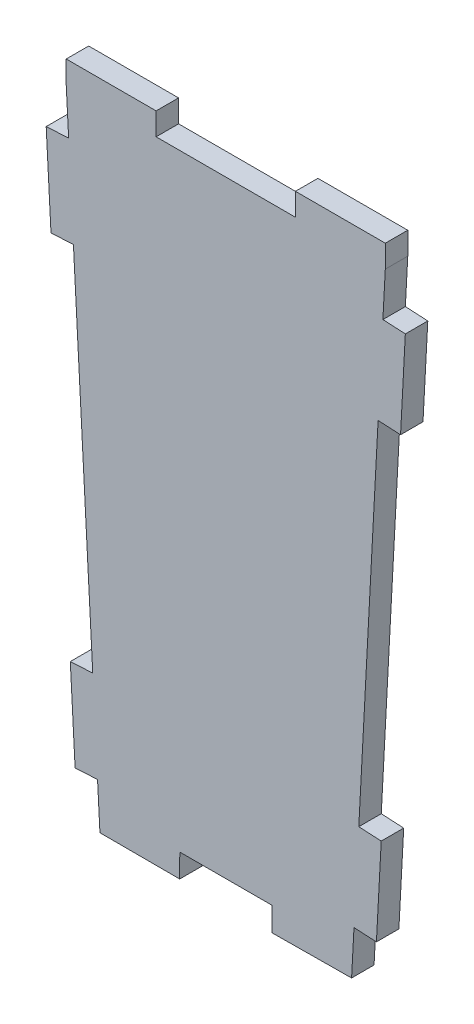
SolidWorks part; units mm, degrees
ref_plane "Front Plane" through (0, 0, 0) normal (0, 0, 1) x (1, 0, 0)
ref_plane "Top Plane" through (0, 0, 0) normal (0, 1, 0) x (1, 0, 0)
ref_plane "Right Plane" through (0, 0, 0) normal (1, 0, 0) x (0, 0, -1)
sketch "Model" plane through (0, 0, 0) normal (0, 0, 1) x (1, 0, 0)
  line L0 (624.1056, -123.6795) -> (619.8071, -43.234)
  line L1 (663.9688, -153.7844) -> (663.9688, -148.4763)
  line L2 (614.8142, -43.5008) -> (619.8071, -43.234)
  line L3 (643.4573, -153.686) -> (625.7069, -153.6468)
  line L4 (625.7069, -153.6468) -> (625.1727, -143.651)
  line L5 (619.1127, -123.9463) -> (624.1056, -123.6795)
  line L6 (669.2063, -13.2767) -> (638.2063, -13.2767)
  line L7 (620.1799, -143.9178) -> (619.1127, -123.9463)
  line L8 (693.6656, -23.5293) -> (692.5984, -43.5008)
  line L9 (689.2063, -13.2767) -> (688.6727, -23.2625)
  line L10 (618.7399, -23.2625) -> (613.747, -23.5293)
  line L11 (681.7063, -153.6367) -> (663.9688, -153.7844)
  line L12 (669.2063, -8.2767) -> (669.2063, -13.2767)
  line L13 (682.2399, -143.651) -> (687.2327, -143.9178)
  line L14 (613.747, -23.5293) -> (614.8142, -43.5008)
  line L15 (681.7063, -153.6367) -> (682.2399, -143.651)
  line L16 (687.2327, -143.9178) -> (688.2999, -123.9463)
  line L17 (688.2999, -123.9463) -> (683.307, -123.6795)
  line L18 (683.307, -123.6795) -> (687.6056, -43.234)
  line L19 (692.5984, -43.5008) -> (687.6056, -43.234)
  line L20 (688.6727, -23.2625) -> (693.6656, -23.5293)
  line L21 (689.2063, -13.2767) -> (689.2063, -8.2767)
  line L22 (689.2063, -8.2767) -> (669.2063, -8.2767)
  line L23 (638.2063, -8.2767) -> (638.2063, -13.2767)
  line L24 (618.2063, -8.2767) -> (638.2063, -8.2767)
  line L25 (618.2063, -13.2767) -> (618.2063, -8.2767)
  line L26 (618.2063, -13.2767) -> (618.7399, -23.2625)
  line L27 (625.1727, -143.651) -> (620.1799, -143.9178)
  line L28 (643.4688, -148.483) -> (643.4573, -153.686)
  line L29 (663.9688, -148.4763) -> (643.4688, -148.483)
  line L30 (658.0332, -74.751) -> (657.5462, -75.0663)
  line L31 (661.2425, -82.805) -> (661.7202, -82.499)
  line L32 (653.6499, -83.0922) -> (652.7679, -83.0219)
  line L33 (661.8794, -82.1307) -> (661.8794, -75.4378)
  line L34 (661.7202, -82.499) -> (661.8396, -82.3227)
  line L35 (657.4244, -82.318) -> (657.5462, -82.4928)
  line L36 (659.6316, -83.0922) -> (658.7638, -83.0204)
  line L37 (657.5462, -75.0663) -> (657.4244, -75.2451)
  line L38 (657.3838, -75.4378) -> (657.3838, -76.0497)
  line L39 (651.4021, -75.4378) -> (651.4423, -75.2455)
  line L40 (658.7638, -83.0204) -> (658.0332, -82.805)
  line L41 (661.8794, -75.4378) -> (661.8396, -75.2404)
  line L42 (661.2425, -74.751) -> (660.5214, -74.545)
  line L43 (655.737, -82.5006) -> (655.2546, -82.8112)
  line L44 (657.4244, -82.318) -> (657.3838, -82.1307)
  line L45 (654.5319, -83.0219) -> (653.6499, -83.0922)
  line L46 (652.7679, -83.0219) -> (652.0452, -82.8112)
  line L47 (651.4021, -81.5188) -> (651.4021, -82.1307)
  line L48 (659.6316, -83.0922) -> (660.5089, -83.0204)
  line L49 (654.5319, -83.0219) -> (655.2546, -82.8112)
  line L50 (655.737, -82.5006) -> (655.8575, -82.323)
  line L51 (655.8575, -82.323) -> (655.8977, -82.1307)
  line L52 (655.8977, -82.1307) -> (655.8977, -75.4378)
  line L53 (651.4021, -82.1307) -> (651.4423, -82.323)
  line L54 (657.3838, -82.1307) -> (657.3838, -81.5188)
  line L55 (659.6316, -74.4763) -> (658.745, -74.545)
  line L56 (661.8396, -82.3227) -> (661.8794, -82.1307)
  line L57 (658.745, -74.545) -> (658.0332, -74.751)
  line L58 (657.4244, -75.2451) -> (657.3838, -75.4378)
  line L59 (657.5462, -82.4928) -> (658.0332, -82.805)
  line L60 (651.5629, -82.5006) -> (651.4423, -82.323)
  line L61 (660.5214, -74.545) -> (659.6316, -74.4763)
  line L62 (660.5089, -83.0204) -> (661.2425, -82.805)
  line L63 (661.8396, -75.2404) -> (661.7202, -75.0601)
  line L64 (661.7202, -75.0601) -> (661.2425, -74.751)
  line L65 (651.5629, -82.5006) -> (652.0452, -82.8112)
  line L66 (651.5629, -75.0679) -> (651.4423, -75.2455)
  line L67 (646.774, -74.5466) -> (647.656, -74.4763)
  line L68 (646.0513, -74.7573) -> (646.774, -74.5466)
  line L69 (652.7679, -74.5466) -> (652.0452, -74.7573)
  line L70 (647.656, -74.4763) -> (648.538, -74.5466)
  line L71 (649.7431, -75.0679) -> (649.2607, -74.7573)
  line L72 (655.737, -75.0679) -> (655.2546, -74.7573)
  line L73 (655.8575, -75.2455) -> (655.737, -75.0679)
  line L74 (649.4668, -79.368) -> (649.0047, -79.6209)
  line L75 (647.656, -79.8207) -> (646.774, -79.7505)
  line L76 (649.8636, -75.2455) -> (649.7431, -75.0679)
  line L77 (646.0513, -79.5398) -> (645.569, -79.2291)
  line L78 (652.0452, -74.7573) -> (651.5629, -75.0679)
  line L79 (645.569, -79.2291) -> (645.4484, -79.0516)
  line L80 (649.9038, -75.4378) -> (649.8636, -75.2455)
  line L81 (645.4082, -75.4378) -> (645.4484, -75.2455)
  line L82 (655.2546, -74.7573) -> (654.5319, -74.5466)
  line L83 (651.4021, -78.7843) -> (651.4021, -75.4378)
  line L84 (646.0513, -74.7573) -> (645.569, -75.0679)
  line L85 (645.5581, -83.0922) -> (649.9038, -83.0922)
  line L86 (649.0047, -79.6209) -> (647.656, -79.8207)
  line L87 (645.4484, -75.2455) -> (645.569, -75.0679)
  line L88 (654.5319, -74.5466) -> (653.6499, -74.4763)
  line L89 (645.4082, -75.4378) -> (645.4082, -78.8591)
  line L90 (653.625, -78.7843) -> (651.4021, -78.7843)
  line L91 (649.9038, -83.0922) -> (649.9038, -78.8591)
  line L92 (646.0513, -79.5398) -> (646.774, -79.7505)
  line L93 (645.4484, -79.0516) -> (645.4082, -78.8591)
  line L94 (653.6499, -74.4763) -> (652.7679, -74.5466)
  line L95 (648.538, -74.5466) -> (649.2607, -74.7573)
  line L96 (649.9038, -78.8591) -> (649.4668, -79.368)
  line L97 (655.8977, -75.4378) -> (655.8575, -75.2455)
  line L98 (660.2799, -72.4763) -> (660.82, -72.4763)
  line L99 (660.82, -72.4763) -> (659.7492, -72.4763)
  line L100 (659.7492, -72.4763) -> (660.2799, -72.4763)
  line L101 (660.2799, -72.4763) -> (660.2799, -70.3224)
  line L102 (660.2799, -70.3224) -> (660.2799, -72.4763)
  line L103 (659.3215, -70.3224) -> (659.3215, -72.4763)
  line L104 (659.3215, -72.4763) -> (659.3215, -71.4149)
  line L105 (659.3215, -71.4149) -> (658.2039, -71.4149)
  line L106 (658.2039, -71.4149) -> (658.2039, -72.4763)
  line L107 (658.2039, -72.4763) -> (658.2039, -70.3224)
  line L108 (658.2039, -70.3224) -> (658.2039, -71.415)
  line L109 (658.2039, -71.415) -> (659.3215, -71.415)
  line L110 (659.3215, -71.415) -> (659.3215, -70.3224)
  line L111 (657.823, -72.4794) -> (657.823, -70.3224)
  line L112 (657.323, -70.7157) -> (657.323, -70.5627)
  line L113 (657.323, -70.5627) -> (657.313, -70.5146)
  line L114 (657.313, -70.5146) -> (657.2829, -70.4703)
  line L115 (657.2829, -70.4703) -> (657.1623, -70.3926)
  line L116 (657.1623, -70.3926) -> (656.9816, -70.3399)
  line L117 (656.9816, -70.3399) -> (656.7611, -70.3224)
  line L118 (656.7611, -70.3224) -> (656.5406, -70.3399)
  line L119 (656.5406, -70.3399) -> (656.3599, -70.3926)
  line L120 (656.3599, -70.3926) -> (656.2393, -70.4703)
  line L121 (656.2393, -70.4703) -> (656.2092, -70.5146)
  line L122 (656.2092, -70.5146) -> (656.1991, -70.5627)
  line L123 (656.1991, -70.5627) -> (656.1929, -71.1996)
  line L124 (656.1929, -71.1996) -> (656.2211, -71.3254)
  line L125 (656.2211, -71.3254) -> (656.3026, -71.4157)
  line L126 (656.3026, -71.4157) -> (656.4373, -71.4706)
  line L127 (656.4373, -71.4706) -> (656.6253, -71.4899)
  line L128 (656.6253, -71.4899) -> (656.966, -71.4985)
  line L129 (656.966, -71.4985) -> (657.1295, -71.518)
  line L130 (657.1295, -71.518) -> (657.2747, -71.5999)
  line L131 (657.2747, -71.5999) -> (657.311, -71.6485)
  line L132 (657.311, -71.6485) -> (657.323, -71.7022)
  line L133 (657.323, -71.7022) -> (657.323, -72.2359)
  line L134 (657.323, -72.2359) -> (657.313, -72.284)
  line L135 (657.313, -72.284) -> (657.2829, -72.3284)
  line L136 (657.2829, -72.3284) -> (657.1623, -72.4061)
  line L137 (657.1623, -72.4061) -> (656.9816, -72.4588)
  line L138 (656.9816, -72.4588) -> (656.7611, -72.4763)
  line L139 (656.7611, -72.4763) -> (656.5406, -72.4588)
  line L140 (656.5406, -72.4588) -> (656.3599, -72.4061)
  line L141 (656.3599, -72.4061) -> (656.2393, -72.3284)
  line L142 (656.2393, -72.3284) -> (656.2092, -72.284)
  line L143 (656.2092, -72.284) -> (656.1991, -72.2359)
  line L144 (656.1991, -72.2359) -> (656.1991, -72.083)
  line L145 (656.1991, -72.083) -> (656.1991, -72.2359)
  line L146 (656.1991, -72.2359) -> (656.2092, -72.284)
  line L147 (656.2092, -72.284) -> (656.2393, -72.3284)
  line L148 (656.2393, -72.3284) -> (656.3599, -72.4061)
  line L149 (656.3599, -72.4061) -> (656.5406, -72.4588)
  line L150 (656.5406, -72.4588) -> (656.7611, -72.4763)
  line L151 (656.7611, -72.4763) -> (656.9816, -72.4588)
  line L152 (656.9816, -72.4588) -> (657.1623, -72.4061)
  line L153 (657.1623, -72.4061) -> (657.2829, -72.3284)
  line L154 (657.2829, -72.3284) -> (657.313, -72.284)
  line L155 (657.313, -72.284) -> (657.323, -72.2359)
  line L156 (657.323, -72.2359) -> (657.323, -71.7022)
  line L157 (657.323, -71.7022) -> (657.311, -71.6485)
  line L158 (657.311, -71.6485) -> (657.2747, -71.5999)
  line L159 (657.2747, -71.5999) -> (657.1295, -71.518)
  line L160 (657.1295, -71.518) -> (656.966, -71.4985)
  line L161 (656.966, -71.4985) -> (656.6253, -71.4899)
  line L162 (656.6253, -71.4899) -> (656.4373, -71.4706)
  line L163 (656.4373, -71.4706) -> (656.3026, -71.4157)
  line L164 (656.3026, -71.4157) -> (656.2211, -71.3254)
  line L165 (656.2211, -71.3254) -> (656.1929, -71.1996)
  line L166 (656.1929, -71.1996) -> (656.1991, -70.5627)
  line L167 (656.1991, -70.5627) -> (656.2092, -70.5146)
  line L168 (656.2092, -70.5146) -> (656.2393, -70.4703)
  line L169 (656.2393, -70.4703) -> (656.3599, -70.3926)
  line L170 (656.3599, -70.3926) -> (656.5406, -70.3399)
  line L171 (656.5406, -70.3399) -> (656.7611, -70.3224)
  line L172 (656.7611, -70.3224) -> (656.9816, -70.3399)
  line L173 (656.9816, -70.3399) -> (657.1623, -70.3926)
  line L174 (657.1623, -70.3926) -> (657.2829, -70.4703)
  line L175 (657.2829, -70.4703) -> (657.313, -70.5146)
  line L176 (657.313, -70.5146) -> (657.323, -70.5627)
  line L177 (657.323, -70.5627) -> (657.323, -70.7157)
  line L178 (654.5791, -70.7157) -> (654.5791, -70.5627)
  line L179 (654.5791, -70.5627) -> (654.5691, -70.5146)
  line L180 (654.5691, -70.5146) -> (654.539, -70.4703)
  line L181 (654.539, -70.4703) -> (654.4184, -70.3926)
  line L182 (654.4184, -70.3926) -> (654.2377, -70.3399)
  line L183 (654.2377, -70.3399) -> (654.0172, -70.3224)
  line L184 (654.0172, -70.3224) -> (653.7967, -70.3399)
  line L185 (653.7967, -70.3399) -> (653.616, -70.3926)
  line L186 (653.616, -70.3926) -> (653.4954, -70.4703)
  line L187 (653.4954, -70.4703) -> (653.4653, -70.5146)
  line L188 (653.4653, -70.5146) -> (653.4552, -70.5627)
  line L189 (653.4552, -70.5627) -> (653.449, -71.1996)
  line L190 (653.449, -71.1996) -> (653.4772, -71.3254)
  line L191 (653.4772, -71.3254) -> (653.5587, -71.4157)
  line L192 (653.5587, -71.4157) -> (653.6934, -71.4706)
  line L193 (653.6934, -71.4706) -> (653.8814, -71.4899)
  line L194 (653.8814, -71.4899) -> (654.2221, -71.4985)
  line L195 (654.2221, -71.4985) -> (654.3856, -71.518)
  line L196 (654.3856, -71.518) -> (654.5308, -71.5999)
  line L197 (654.5308, -71.5999) -> (654.567, -71.6485)
  line L198 (654.567, -71.6485) -> (654.5791, -71.7022)
  line L199 (654.5791, -71.7022) -> (654.5791, -72.2359)
  line L200 (654.5791, -72.2359) -> (654.5691, -72.284)
  line L201 (654.5691, -72.284) -> (654.539, -72.3284)
  line L202 (654.539, -72.3284) -> (654.4184, -72.4061)
  line L203 (654.4184, -72.4061) -> (654.2377, -72.4588)
  line L204 (654.2377, -72.4588) -> (654.0172, -72.4763)
  line L205 (654.0172, -72.4763) -> (653.7967, -72.4588)
  line L206 (653.7967, -72.4588) -> (653.616, -72.4061)
  line L207 (653.616, -72.4061) -> (653.4954, -72.3284)
  line L208 (653.4954, -72.3284) -> (653.4653, -72.284)
  line L209 (653.4653, -72.284) -> (653.4552, -72.2359)
  line L210 (653.4552, -72.2359) -> (653.4552, -72.083)
  line L211 (653.4552, -72.083) -> (653.4552, -72.2359)
  line L212 (653.4552, -72.2359) -> (653.4653, -72.284)
  line L213 (653.4653, -72.284) -> (653.4954, -72.3284)
  line L214 (653.4954, -72.3284) -> (653.616, -72.4061)
  line L215 (653.616, -72.4061) -> (653.7967, -72.4588)
  line L216 (653.7967, -72.4588) -> (654.0172, -72.4763)
  line L217 (654.0172, -72.4763) -> (654.2377, -72.4588)
  line L218 (654.2377, -72.4588) -> (654.4184, -72.4061)
  line L219 (654.4184, -72.4061) -> (654.539, -72.3284)
  line L220 (654.539, -72.3284) -> (654.5691, -72.284)
  line L221 (654.5691, -72.284) -> (654.5791, -72.2359)
  line L222 (654.5791, -72.2359) -> (654.5791, -71.7022)
  line L223 (654.5791, -71.7022) -> (654.567, -71.6485)
  line L224 (654.567, -71.6485) -> (654.5308, -71.5999)
  line L225 (654.5308, -71.5999) -> (654.3856, -71.518)
  line L226 (654.3856, -71.518) -> (654.2221, -71.4985)
  line L227 (654.2221, -71.4985) -> (653.8814, -71.4899)
  line L228 (653.8814, -71.4899) -> (653.6934, -71.4706)
  line L229 (653.6934, -71.4706) -> (653.5587, -71.4157)
  line L230 (653.5587, -71.4157) -> (653.4772, -71.3254)
  line L231 (653.4772, -71.3254) -> (653.449, -71.1996)
  line L232 (653.449, -71.1996) -> (653.4552, -70.5627)
  line L233 (653.4552, -70.5627) -> (653.4653, -70.5146)
  line L234 (653.4653, -70.5146) -> (653.4954, -70.4703)
  line L235 (653.4954, -70.4703) -> (653.616, -70.3926)
  line L236 (653.616, -70.3926) -> (653.7967, -70.3399)
  line L237 (653.7967, -70.3399) -> (654.0172, -70.3224)
  line L238 (654.0172, -70.3224) -> (654.2377, -70.3399)
  line L239 (654.2377, -70.3399) -> (654.4184, -70.3926)
  line L240 (654.4184, -70.3926) -> (654.539, -70.4703)
  line L241 (654.539, -70.4703) -> (654.5691, -70.5146)
  line L242 (654.5691, -70.5146) -> (654.5791, -70.5627)
  line L243 (654.5791, -70.5627) -> (654.5791, -70.7157)
  line L244 (653.0837, -72.4794) -> (653.0837, -70.3224)
  line L245 (652.5837, -70.3224) -> (652.5837, -72.4763)
  line L246 (652.5837, -72.4763) -> (652.0748, -72.4763)
  line L247 (652.0748, -72.4763) -> (651.8579, -72.4584)
  line L248 (651.8579, -72.4584) -> (651.6752, -72.4045)
  line L249 (651.6752, -72.4045) -> (651.5535, -72.3265)
  line L250 (651.5535, -72.3265) -> (651.523, -72.2828)
  line L251 (651.523, -72.2828) -> (651.5129, -72.2359)
  line L252 (651.5129, -72.2359) -> (651.5129, -70.5627)
  line L253 (651.5129, -70.5627) -> (651.523, -70.5145)
  line L254 (651.523, -70.5145) -> (651.5535, -70.4699)
  line L255 (651.5535, -70.4699) -> (651.6752, -70.391)
  line L256 (651.6752, -70.391) -> (651.8532, -70.3395)
  line L257 (651.8532, -70.3395) -> (652.0748, -70.3224)
  line L258 (652.0748, -70.3224) -> (652.5837, -70.3224)
  line L259 (652.5837, -72.4763) -> (652.5837, -70.3224)
  line L260 (652.5837, -70.3224) -> (652.0748, -70.3224)
  line L261 (652.0748, -70.3224) -> (651.8532, -70.3395)
  line L262 (651.8532, -70.3395) -> (651.6752, -70.391)
  line L263 (651.6752, -70.391) -> (651.5535, -70.4699)
  line L264 (651.5535, -70.4699) -> (651.523, -70.5145)
  line L265 (651.523, -70.5145) -> (651.5129, -70.5627)
  line L266 (651.5129, -70.5627) -> (651.5129, -72.2359)
  line L267 (651.5129, -72.2359) -> (651.523, -72.2828)
  line L268 (651.523, -72.2828) -> (651.5535, -72.3265)
  line L269 (651.5535, -72.3265) -> (651.6752, -72.4045)
  line L270 (651.6752, -72.4045) -> (651.8579, -72.4584)
  line L271 (651.8579, -72.4584) -> (652.0748, -72.4763)
  line L272 (652.0748, -72.4763) -> (652.5837, -72.4763)
  line L273 (651.0852, -70.3224) -> (651.0852, -72.4763)
  line L274 (651.0852, -72.4763) -> (650.0206, -72.4763)
  line L275 (650.0206, -72.4763) -> (651.0852, -72.4763)
  line L276 (651.0852, -72.4763) -> (651.0852, -71.4306)
  line L277 (651.0852, -71.4306) -> (650.1705, -71.4306)
  line L278 (650.1705, -71.4306) -> (651.0852, -71.4306)
  line L279 (651.0852, -71.4306) -> (651.0852, -70.3224)
  line L280 (651.0852, -70.3224) -> (650.0206, -70.3224)
  line L281 (650.0206, -70.3224) -> (651.0852, -70.3224)
  line L282 (648.3383, -72.4794) -> (648.3383, -70.3224)
  line L283 (647.8383, -70.3224) -> (647.8383, -72.4763)
  line L284 (647.8383, -72.4763) -> (646.7581, -70.3224)
  line L285 (646.7581, -70.3224) -> (646.7581, -72.4763)
  line L286 (646.7581, -72.4763) -> (646.7581, -70.3224)
  line L287 (646.7581, -70.3224) -> (647.8383, -72.4763)
  line L288 (647.8383, -72.4763) -> (647.8383, -70.3224)
  line L289 (661.8794, -73.4763) -> (645.5581, -73.4763)
  line L290 (629.4678, -131.9185) -> (629.8292, -131.8132)
  line L291 (629.8292, -131.8132) -> (630.2702, -131.778)
  line L292 (634.391, -133.957) -> (634.391, -136.086)
  line L293 (635.1341, -135.2993) -> (635.1341, -135.6052)
  line L294 (631.3137, -132.0738) -> (631.374, -132.1626)
  line L295 (631.0725, -131.9185) -> (631.3137, -132.0738)
  line L296 (634.391, -131.778) -> (634.391, -133.957)
  line L297 (632.5616, -133.957) -> (634.391, -133.957)
  line L298 (632.2619, -136.086) -> (634.391, -136.086)
  line L299 (631.3941, -132.2588) -> (631.374, -132.1626)
  line L300 (635.1544, -135.6989) -> (635.1341, -135.6052)
  line L301 (629.1463, -132.2588) -> (629.1664, -132.1626)
  line L302 (629.1664, -132.1626) -> (629.2267, -132.0738)
  line L303 (629.2267, -132.0738) -> (629.4678, -131.9185)
  line L304 (629.2267, -134.1545) -> (629.1664, -134.0657)
  line L305 (629.1664, -134.0657) -> (629.1463, -133.9695)
  line L306 (629.1463, -133.9695) -> (629.1463, -132.2588)
  line L307 (630.9445, -134.3503) -> (631.1756, -134.2239)
  line L308 (630.2702, -134.4503) -> (629.8292, -134.4151)
  line L309 (629.8292, -134.4151) -> (629.4678, -134.3098)
  line L310 (629.4678, -134.3098) -> (629.2267, -134.1545)
  line L311 (629.2212, -136.086) -> (631.3941, -136.086)
  line L312 (631.3941, -136.086) -> (631.3941, -133.9695)
  line L313 (631.3941, -133.9695) -> (631.1756, -134.2239)
  line L314 (630.2702, -134.4503) -> (630.9445, -134.3503)
  line L315 (630.2702, -131.778) -> (630.7112, -131.8132)
  line L316 (630.7112, -131.8132) -> (631.0725, -131.9185)
  line L317 (635.1544, -132.1624) -> (635.2153, -132.0731)
  line L318 (637.0634, -131.9154) -> (637.3023, -132.0699)
  line L319 (637.362, -132.1601) -> (637.3819, -132.2588)
  line L320 (637.3819, -132.2588) -> (637.3819, -135.6052)
  line L321 (635.1341, -132.5647) -> (635.1341, -132.2588)
  line L322 (635.8147, -131.8124) -> (636.258, -131.778)
  line L323 (636.258, -131.778) -> (636.7029, -131.8124)
  line L324 (637.3819, -135.6052) -> (637.362, -135.7012)
  line L325 (637.362, -135.7012) -> (637.3023, -135.7894)
  line L326 (637.3023, -135.7894) -> (637.0634, -135.9424)
  line L327 (637.0634, -135.9424) -> (636.6966, -136.0501)
  line L328 (636.258, -136.086) -> (635.8241, -136.0501)
  line L329 (635.1341, -132.2588) -> (635.1544, -132.1624)
  line L330 (636.7029, -131.8124) -> (637.0634, -131.9154)
  line L331 (637.3023, -132.0699) -> (637.362, -132.1601)
  line L332 (636.6966, -136.0501) -> (636.258, -136.086)
  line L333 (635.2153, -132.0731) -> (635.4588, -131.9154)
  line L334 (635.4588, -131.9154) -> (635.8147, -131.8124)
  line L335 (635.8241, -136.0501) -> (635.4588, -135.9424)
  line L336 (635.4588, -135.9424) -> (635.2153, -135.7863)
  line L337 (635.2153, -135.7863) -> (635.1544, -135.6989)
  line L338 (626.6463, -133.932) -> (621.6463, -133.932)
  line L339 (623.6463, -132.932) -> (621.6463, -133.932)
  line L340 (623.6463, -134.932) -> (621.6463, -133.932)
  line L341 (624.1022, -31.5015) -> (624.4635, -31.3962)
  line L342 (624.4635, -31.3962) -> (624.9045, -31.3611)
  line L343 (629.0254, -33.54) -> (629.0254, -35.669)
  line L344 (629.7684, -34.8823) -> (629.7684, -35.1882)
  line L345 (625.948, -31.6569) -> (626.0083, -31.7456)
  line L346 (625.7069, -31.5015) -> (625.948, -31.6569)
  line L347 (629.0254, -31.3611) -> (629.0254, -33.54)
  line L348 (627.1959, -33.54) -> (629.0254, -33.54)
  line L349 (626.8962, -35.669) -> (629.0254, -35.669)
  line L350 (626.0284, -31.8418) -> (626.0083, -31.7456)
  line L351 (629.7887, -35.2819) -> (629.7684, -35.1882)
  line L352 (623.7806, -31.8418) -> (623.8007, -31.7456)
  line L353 (623.8007, -31.7456) -> (623.861, -31.6569)
  line L354 (623.861, -31.6569) -> (624.1022, -31.5015)
  line L355 (623.861, -33.7375) -> (623.8007, -33.6487)
  line L356 (623.8007, -33.6487) -> (623.7806, -33.5525)
  line L357 (623.7806, -33.5525) -> (623.7806, -31.8418)
  line L358 (625.5789, -33.9334) -> (625.8099, -33.8069)
  line L359 (624.9045, -34.0333) -> (624.4635, -33.9982)
  line L360 (624.4635, -33.9982) -> (624.1022, -33.8928)
  line L361 (624.1022, -33.8928) -> (623.861, -33.7375)
  line L362 (623.8555, -35.669) -> (626.0284, -35.669)
  line L363 (626.0284, -35.669) -> (626.0284, -33.5525)
  line L364 (626.0284, -33.5525) -> (625.8099, -33.8069)
  line L365 (624.9045, -34.0333) -> (625.5789, -33.9334)
  line L366 (624.9045, -31.3611) -> (625.3455, -31.3962)
  line L367 (625.3455, -31.3962) -> (625.7069, -31.5015)
  line L368 (629.7887, -31.7454) -> (629.8496, -31.6561)
  line L369 (631.6978, -31.4984) -> (631.9366, -31.653)
  line L370 (631.9963, -31.7431) -> (632.0162, -31.8418)
  line L371 (632.0162, -31.8418) -> (632.0162, -35.1882)
  line L372 (629.7684, -32.1477) -> (629.7684, -31.8418)
  line L373 (630.449, -31.3954) -> (630.8923, -31.3611)
  line L374 (630.8923, -31.3611) -> (631.3372, -31.3954)
  line L375 (632.0162, -35.1882) -> (631.9963, -35.2842)
  line L376 (631.9963, -35.2842) -> (631.9366, -35.3724)
  line L377 (631.9366, -35.3724) -> (631.6978, -35.5254)
  line L378 (631.6978, -35.5254) -> (631.331, -35.6331)
  line L379 (630.8923, -35.669) -> (630.4584, -35.6331)
  line L380 (629.7684, -31.8418) -> (629.7887, -31.7454)
  line L381 (631.3372, -31.3954) -> (631.6978, -31.4984)
  line L382 (631.9366, -31.653) -> (631.9963, -31.7431)
  line L383 (631.331, -35.6331) -> (630.8923, -35.669)
  line L384 (629.8496, -31.6561) -> (630.0931, -31.4984)
  line L385 (630.0931, -31.4984) -> (630.449, -31.3954)
  line L386 (630.4584, -35.6331) -> (630.0931, -35.5254)
  line L387 (630.0931, -35.5254) -> (629.8496, -35.3693)
  line L388 (629.8496, -35.3693) -> (629.7887, -35.2819)
  line L389 (621.2806, -33.515) -> (616.2806, -33.515)
  line L390 (618.2806, -32.515) -> (616.2806, -33.515)
  line L391 (618.2806, -34.515) -> (616.2806, -33.515)
  line L392 (653.7063, -20.2767) -> (653.7063, -15.2767)
  line L393 (654.7063, -17.2767) -> (653.7063, -15.2767)
  line L394 (652.7063, -17.2767) -> (653.7063, -15.2767)
  line L395 (655.5763, -22.0634) -> (655.5763, -21.7575)
  line L396 (655.5763, -21.7575) -> (655.5966, -21.6611)
  line L397 (655.5966, -21.6611) -> (655.6575, -21.5717)
  line L398 (655.6575, -21.5717) -> (655.901, -21.4141)
  line L399 (655.901, -21.4141) -> (656.2569, -21.3111)
  line L400 (656.2569, -21.3111) -> (656.7002, -21.2767)
  line L401 (656.7002, -21.2767) -> (657.1451, -21.3111)
  line L402 (657.1451, -21.3111) -> (657.5057, -21.4141)
  line L403 (657.5057, -21.4141) -> (657.7445, -21.5686)
  line L404 (657.7445, -21.5686) -> (657.8042, -21.6588)
  line L405 (657.8042, -21.6588) -> (657.8241, -21.7575)
  line L406 (657.8241, -21.7575) -> (657.8241, -25.1039)
  line L407 (657.8241, -25.1039) -> (657.8042, -25.1999)
  line L408 (657.8042, -25.1999) -> (657.7445, -25.2881)
  line L409 (657.7445, -25.2881) -> (657.5057, -25.4411)
  line L410 (657.5057, -25.4411) -> (657.1389, -25.5488)
  line L411 (657.1389, -25.5488) -> (656.7002, -25.5847)
  line L412 (656.7002, -25.5847) -> (656.2663, -25.5488)
  line L413 (656.2663, -25.5488) -> (655.901, -25.4411)
  line L414 (655.901, -25.4411) -> (655.6575, -25.285)
  line L415 (655.6575, -25.285) -> (655.5966, -25.1976)
  line L416 (655.5966, -25.1976) -> (655.5763, -25.1039)
  line L417 (655.5763, -25.1039) -> (655.5763, -24.798)
  line L418 (655.5763, -24.798) -> (655.5763, -25.1039)
  line L419 (655.5763, -25.1039) -> (655.5966, -25.1976)
  line L420 (655.5966, -25.1976) -> (655.6575, -25.285)
  line L421 (655.6575, -25.285) -> (655.901, -25.4411)
  line L422 (655.901, -25.4411) -> (656.2663, -25.5488)
  line L423 (656.2663, -25.5488) -> (656.7002, -25.5847)
  line L424 (656.7002, -25.5847) -> (657.1389, -25.5488)
  line L425 (657.1389, -25.5488) -> (657.5057, -25.4411)
  line L426 (657.5057, -25.4411) -> (657.7445, -25.2881)
  line L427 (657.7445, -25.2881) -> (657.8042, -25.1999)
  line L428 (657.8042, -25.1999) -> (657.8241, -25.1039)
  line L429 (657.8241, -25.1039) -> (657.8241, -21.7575)
  line L430 (657.8241, -21.7575) -> (657.8042, -21.6588)
  line L431 (657.8042, -21.6588) -> (657.7445, -21.5686)
  line L432 (657.7445, -21.5686) -> (657.5057, -21.4141)
  line L433 (657.5057, -21.4141) -> (657.1451, -21.3111)
  line L434 (657.1451, -21.3111) -> (656.7002, -21.2767)
  line L435 (656.7002, -21.2767) -> (656.2569, -21.3111)
  line L436 (656.2569, -21.3111) -> (655.901, -21.4141)
  line L437 (655.901, -21.4141) -> (655.6575, -21.5717)
  line L438 (655.6575, -21.5717) -> (655.5966, -21.6611)
  line L439 (655.5966, -21.6611) -> (655.5763, -21.7575)
  line L440 (655.5763, -21.7575) -> (655.5763, -22.0634)
  line L441 (654.8333, -21.2767) -> (654.8333, -25.5847)
  line L442 (654.8333, -25.5847) -> (652.7041, -25.5847)
  line L443 (652.7041, -25.5847) -> (654.8333, -25.5847)
  line L444 (654.8333, -25.5847) -> (654.8333, -23.4931)
  line L445 (654.8333, -23.4931) -> (653.0038, -23.4931)
  line L446 (653.0038, -23.4931) -> (654.8333, -23.4931)
  line L447 (654.8333, -23.4931) -> (654.8333, -21.2767)
  line L448 (654.8333, -21.2767) -> (652.7041, -21.2767)
  line L449 (652.7041, -21.2767) -> (654.8333, -21.2767)
  line L450 (650.7124, -21.2767) -> (651.1534, -21.3119)
  line L451 (651.1534, -21.3119) -> (651.5148, -21.4172)
  line L452 (651.5148, -21.4172) -> (651.7559, -21.5725)
  line L453 (651.7559, -21.5725) -> (651.8162, -21.6613)
  line L454 (651.8162, -21.6613) -> (651.8363, -21.7575)
  line L455 (651.8363, -21.7575) -> (651.8162, -21.6613)
  line L456 (651.8162, -21.6613) -> (651.7559, -21.5725)
  line L457 (651.7559, -21.5725) -> (651.5148, -21.4172)
  line L458 (649.9101, -21.4172) -> (649.6689, -21.5725)
  line L459 (649.6689, -21.5725) -> (649.6086, -21.6613)
  line L460 (649.6086, -21.6613) -> (649.5885, -21.7575)
  line L461 (649.5885, -21.7575) -> (649.5885, -23.4681)
  line L462 (649.5885, -23.4681) -> (649.6086, -23.5643)
  line L463 (649.6086, -23.5643) -> (649.6689, -23.6531)
  line L464 (649.6689, -23.6531) -> (649.9101, -23.8085)
  line L465 (649.9101, -23.8085) -> (650.2714, -23.9138)
  line L466 (650.2714, -23.9138) -> (650.7124, -23.9489)
  line L467 (650.7124, -23.9489) -> (651.3868, -23.849)
  line L468 (651.3868, -23.849) -> (651.6178, -23.7226)
  line L469 (651.6178, -23.7226) -> (651.8363, -23.4681)
  line L470 (651.8363, -23.4681) -> (651.8363, -25.5847)
  line L471 (651.8363, -25.5847) -> (649.6634, -25.5847)
  line L472 (649.6634, -25.5847) -> (651.8363, -25.5847)
  line L473 (651.8363, -25.5847) -> (651.8363, -23.4681)
  line L474 (651.8363, -23.4681) -> (651.6178, -23.7226)
  line L475 (651.6178, -23.7226) -> (651.3868, -23.849)
  line L476 (651.3868, -23.849) -> (650.7124, -23.9489)
  line L477 (650.7124, -23.9489) -> (650.2714, -23.9138)
  line L478 (650.2714, -23.9138) -> (649.9101, -23.8085)
  line L479 (649.9101, -23.8085) -> (649.6689, -23.6531)
  line L480 (649.6689, -23.6531) -> (649.6086, -23.5643)
  line L481 (649.6086, -23.5643) -> (649.5885, -23.4681)
  line L482 (649.5885, -23.4681) -> (649.5885, -21.7575)
  line L483 (649.5885, -21.7575) -> (649.6086, -21.6613)
  line L484 (649.6086, -21.6613) -> (649.6689, -21.5725)
  line L485 (649.6689, -21.5725) -> (649.9101, -21.4172)
  line L486 (649.9101, -21.4172) -> (650.2714, -21.3119)
  line L487 (650.2714, -21.3119) -> (650.7124, -21.2767)
  line L488 (675.7179, -31.5015) -> (676.0793, -31.3962)
  line L489 (676.0793, -31.3962) -> (676.5203, -31.3611)
  line L490 (680.6412, -33.54) -> (680.6412, -35.669)
  line L491 (681.3842, -34.8823) -> (681.3842, -35.1882)
  line L492 (677.5638, -31.6569) -> (677.6241, -31.7456)
  line L493 (677.3227, -31.5015) -> (677.5638, -31.6569)
  line L494 (680.6412, -31.3611) -> (680.6412, -33.54)
  line L495 (678.8117, -33.54) -> (680.6412, -33.54)
  line L496 (678.512, -35.669) -> (680.6412, -35.669)
  line L497 (677.6442, -31.8418) -> (677.6241, -31.7456)
  line L498 (681.4045, -35.2819) -> (681.3842, -35.1882)
  line L499 (675.3964, -31.8418) -> (675.4165, -31.7456)
  line L500 (675.4165, -31.7456) -> (675.4768, -31.6569)
  line L501 (675.4768, -31.6569) -> (675.7179, -31.5015)
  line L502 (675.4768, -33.7375) -> (675.4165, -33.6487)
  line L503 (675.4165, -33.6487) -> (675.3964, -33.5525)
  line L504 (675.3964, -33.5525) -> (675.3964, -31.8418)
  line L505 (677.1947, -33.9334) -> (677.4257, -33.8069)
  line L506 (676.5203, -34.0333) -> (676.0793, -33.9982)
  line L507 (676.0793, -33.9982) -> (675.7179, -33.8928)
  line L508 (675.7179, -33.8928) -> (675.4768, -33.7375)
  line L509 (675.4713, -35.669) -> (677.6442, -35.669)
  line L510 (677.6442, -35.669) -> (677.6442, -33.5525)
  line L511 (677.6442, -33.5525) -> (677.4257, -33.8069)
  line L512 (676.5203, -34.0333) -> (677.1947, -33.9334)
  line L513 (676.5203, -31.3611) -> (676.9613, -31.3962)
  line L514 (676.9613, -31.3962) -> (677.3227, -31.5015)
  line L515 (681.4045, -31.7454) -> (681.4654, -31.6561)
  line L516 (683.3136, -31.4984) -> (683.5524, -31.653)
  line L517 (683.6121, -31.7431) -> (683.632, -31.8418)
  line L518 (683.632, -31.8418) -> (683.632, -35.1882)
  line L519 (681.3842, -32.1477) -> (681.3842, -31.8418)
  line L520 (682.0648, -31.3954) -> (682.5081, -31.3611)
  line L521 (682.5081, -31.3611) -> (682.953, -31.3954)
  line L522 (683.632, -35.1882) -> (683.6121, -35.2842)
  line L523 (683.6121, -35.2842) -> (683.5524, -35.3724)
  line L524 (683.5524, -35.3724) -> (683.3136, -35.5254)
  line L525 (683.3136, -35.5254) -> (682.9467, -35.6331)
  line L526 (682.5081, -35.669) -> (682.0742, -35.6331)
  line L527 (681.3842, -31.8418) -> (681.4045, -31.7454)
  line L528 (682.953, -31.3954) -> (683.3136, -31.4984)
  line L529 (683.5524, -31.653) -> (683.6121, -31.7431)
  line L530 (682.9467, -35.6331) -> (682.5081, -35.669)
  line L531 (681.4654, -31.6561) -> (681.7089, -31.4984)
  line L532 (681.7089, -31.4984) -> (682.0648, -31.3954)
  line L533 (682.0742, -35.6331) -> (681.7089, -35.5254)
  line L534 (681.7089, -35.5254) -> (681.4654, -35.3693)
  line L535 (681.4654, -35.3693) -> (681.4045, -35.2819)
  line L536 (686.132, -33.515) -> (691.132, -33.515)
  line L537 (689.132, -34.515) -> (691.132, -33.515)
  line L538 (689.132, -32.515) -> (691.132, -33.515)
  line L539 (653.7188, -141.4797) -> (653.7188, -146.4797)
  line L540 (652.7188, -144.4797) -> (653.7188, -146.4797)
  line L541 (654.7188, -144.4797) -> (653.7188, -146.4797)
  line L542 (655.9135, -140.3361) -> (656.2787, -140.4438)
  line L543 (657.5181, -136.3091) -> (657.1575, -136.2061)
  line L544 (655.5888, -139.9989) -> (655.609, -140.0926)
  line L545 (656.7127, -140.4797) -> (657.1513, -140.4438)
  line L546 (657.8366, -139.9989) -> (657.8366, -136.6525)
  line L547 (651.8287, -136.5563) -> (651.7684, -136.4675)
  line L548 (649.6759, -140.4797) -> (651.8488, -140.4797)
  line L549 (657.757, -136.4636) -> (657.5181, -136.3091)
  line L550 (652.6104, -140.4797) -> (652.6104, -138.3571)
  line L551 (651.3992, -138.744) -> (650.7249, -138.8439)
  line L552 (657.8167, -140.0949) -> (657.8366, -139.9989)
  line L553 (651.8488, -138.3631) -> (651.6302, -138.6176)
  line L554 (651.8488, -138.3631) -> (651.8488, -140.4797)
  line L555 (649.6813, -138.5481) -> (649.9225, -138.7035)
  line L556 (651.6302, -138.6176) -> (651.3992, -138.744)
  line L557 (655.609, -140.0926) -> (655.6699, -140.18)
  line L558 (657.8366, -136.6525) -> (657.8167, -136.5538)
  line L559 (655.9135, -136.3091) -> (655.6699, -136.4667)
  line L560 (650.7249, -138.8439) -> (650.2839, -138.8088)
  line L561 (656.2787, -140.4438) -> (656.7127, -140.4797)
  line L562 (650.2839, -138.8088) -> (649.9225, -138.7035)
  line L563 (649.6813, -138.5481) -> (649.621, -138.4594)
  line L564 (649.601, -138.3631) -> (649.601, -136.6525)
  line L565 (649.621, -138.4594) -> (649.601, -138.3631)
  line L566 (655.6699, -140.18) -> (655.9135, -140.3361)
  line L567 (657.1575, -136.2061) -> (656.7127, -136.1717)
  line L568 (655.5888, -136.6525) -> (655.5888, -136.9584)
  line L569 (654.8457, -138.3571) -> (652.6104, -138.3571)
  line L570 (654.8457, -138.3571) -> (654.8457, -140.4797)
  line L571 (657.5181, -140.3361) -> (657.757, -140.1831)
  line L572 (655.5888, -139.693) -> (655.5888, -139.9989)
  line L573 (654.8457, -136.1717) -> (654.8457, -138.3571)
  line L574 (656.2693, -136.2061) -> (655.9135, -136.3091)
  line L575 (657.1513, -140.4438) -> (657.5181, -140.3361)
  line L576 (657.757, -140.1831) -> (657.8167, -140.0949)
  line L577 (651.1658, -136.2069) -> (651.5272, -136.3122)
  line L578 (655.609, -136.5561) -> (655.5888, -136.6525)
  line L579 (651.7684, -136.4675) -> (651.5272, -136.3122)
  line L580 (655.6699, -136.4667) -> (655.609, -136.5561)
  line L581 (656.7127, -136.1717) -> (656.2693, -136.2061)
  line L582 (651.8488, -136.6525) -> (651.8287, -136.5563)
  line L583 (657.8167, -136.5538) -> (657.757, -136.4636)
  line L584 (650.7249, -136.1717) -> (651.1658, -136.2069)
  line L585 (649.6813, -136.4675) -> (649.9225, -136.3122)
  line L586 (650.2839, -136.2069) -> (650.7249, -136.1717)
  line L587 (649.621, -136.5563) -> (649.6813, -136.4675)
  line L588 (649.9225, -136.3122) -> (650.2839, -136.2069)
  line L589 (652.6104, -138.3571) -> (652.6104, -136.1717)
  line L590 (649.601, -136.6525) -> (649.621, -136.5563)
  line L591 (670.3523, -131.9185) -> (670.7136, -131.8132)
  line L592 (670.7136, -131.8132) -> (671.1546, -131.778)
  line L593 (675.2755, -133.957) -> (675.2755, -136.086)
  line L594 (676.0185, -135.2993) -> (676.0185, -135.6052)
  line L595 (672.1981, -132.0738) -> (672.2584, -132.1626)
  line L596 (671.957, -131.9185) -> (672.1981, -132.0738)
  line L597 (675.2755, -131.778) -> (675.2755, -133.957)
  line L598 (673.446, -133.957) -> (675.2755, -133.957)
  line L599 (673.1463, -136.086) -> (675.2755, -136.086)
  line L600 (672.2785, -132.2588) -> (672.2584, -132.1626)
  line L601 (676.0388, -135.6989) -> (676.0185, -135.6052)
  line L602 (670.0307, -132.2588) -> (670.0508, -132.1626)
  line L603 (670.0508, -132.1626) -> (670.1111, -132.0738)
  line L604 (670.1111, -132.0738) -> (670.3523, -131.9185)
  line L605 (670.1111, -134.1545) -> (670.0508, -134.0657)
  line L606 (670.0508, -134.0657) -> (670.0307, -133.9695)
  line L607 (670.0307, -133.9695) -> (670.0307, -132.2588)
  line L608 (671.829, -134.3503) -> (672.06, -134.2239)
  line L609 (671.1546, -134.4503) -> (670.7136, -134.4151)
  line L610 (670.7136, -134.4151) -> (670.3523, -134.3098)
  line L611 (670.3523, -134.3098) -> (670.1111, -134.1545)
  line L612 (670.1056, -136.086) -> (672.2785, -136.086)
  line L613 (672.2785, -136.086) -> (672.2785, -133.9695)
  line L614 (672.2785, -133.9695) -> (672.06, -134.2239)
  line L615 (671.1546, -134.4503) -> (671.829, -134.3503)
  line L616 (671.1546, -131.778) -> (671.5956, -131.8132)
  line L617 (671.5956, -131.8132) -> (671.957, -131.9185)
  line L618 (676.0388, -132.1624) -> (676.0997, -132.0731)
  line L619 (677.9479, -131.9154) -> (678.1867, -132.0699)
  line L620 (678.2464, -132.1601) -> (678.2663, -132.2588)
  line L621 (678.2663, -132.2588) -> (678.2663, -135.6052)
  line L622 (676.0185, -132.5647) -> (676.0185, -132.2588)
  line L623 (676.6991, -131.8124) -> (677.1424, -131.778)
  line L624 (677.1424, -131.778) -> (677.5873, -131.8124)
  line L625 (678.2663, -135.6052) -> (678.2464, -135.7012)
  line L626 (678.2464, -135.7012) -> (678.1867, -135.7894)
  line L627 (678.1867, -135.7894) -> (677.9479, -135.9424)
  line L628 (677.9479, -135.9424) -> (677.5811, -136.0501)
  line L629 (677.1424, -136.086) -> (676.7085, -136.0501)
  line L630 (676.0185, -132.2588) -> (676.0388, -132.1624)
  line L631 (677.5873, -131.8124) -> (677.9479, -131.9154)
  line L632 (678.1867, -132.0699) -> (678.2464, -132.1601)
  line L633 (677.5811, -136.0501) -> (677.1424, -136.086)
  line L634 (676.0997, -132.0731) -> (676.3432, -131.9154)
  line L635 (676.3432, -131.9154) -> (676.6991, -131.8124)
  line L636 (676.7085, -136.0501) -> (676.3432, -135.9424)
  line L637 (676.3432, -135.9424) -> (676.0997, -135.7863)
  line L638 (676.0997, -135.7863) -> (676.0388, -135.6989)
  line L639 (680.7663, -133.932) -> (685.7663, -133.932)
  line L640 (683.7663, -134.932) -> (685.7663, -133.932)
  line L641 (683.7663, -132.932) -> (685.7663, -133.932)
sketch "Sketch2" plane through (0, 0, 0) normal (0, 0, 1) x (1, 0, 0)
  line L0 (681.7063, -153.6367) -> (682.2399, -143.651) construction
  line L1 (682.2399, -143.651) -> (687.2327, -143.9178) construction
  line L2 (687.2327, -143.9178) -> (688.2999, -123.9463) construction
  line L3 (688.2999, -123.9463) -> (683.307, -123.6795) construction
  line L4 (683.307, -123.6795) -> (687.6056, -43.234) construction
  line L5 (692.5984, -43.5008) -> (687.6056, -43.234) construction
  line L6 (693.6656, -23.5293) -> (692.5984, -43.5008) construction
  line L7 (688.6727, -23.2625) -> (693.6656, -23.5293) construction
  line L8 (689.2063, -13.2767) -> (688.6727, -23.2625) construction
  line L9 (689.2063, -13.2767) -> (689.2063, -8.2767) construction
  line L10 (689.2063, -8.2767) -> (669.2063, -8.2767) construction
  line L11 (669.2063, -8.2767) -> (669.2063, -13.2767) construction
  line L12 (669.2063, -13.2767) -> (638.2063, -13.2767) construction
  line L13 (638.2063, -8.2767) -> (638.2063, -13.2767) construction
  line L14 (618.2063, -8.2767) -> (638.2063, -8.2767) construction
  line L15 (618.2063, -13.2767) -> (618.2063, -8.2767) construction
  line L16 (618.2063, -13.2767) -> (618.7399, -23.2625) construction
  line L17 (618.7399, -23.2625) -> (613.747, -23.5293) construction
  line L18 (613.747, -23.5293) -> (614.8142, -43.5008) construction
  line L19 (614.8142, -43.5008) -> (619.8071, -43.234) construction
  line L20 (624.1056, -123.6795) -> (619.8071, -43.234) construction
  line L21 (619.1127, -123.9463) -> (624.1056, -123.6795) construction
  line L22 (620.1799, -143.9178) -> (619.1127, -123.9463) construction
  line L23 (625.1727, -143.651) -> (620.1799, -143.9178) construction
  line L24 (625.7069, -153.6468) -> (625.1727, -143.651) construction
  line L25 (643.4573, -153.686) -> (625.7069, -153.6468) construction
  line L26 (643.4688, -148.483) -> (643.4573, -153.686) construction
  line L27 (663.9688, -148.4763) -> (643.4688, -148.483) construction
  line L28 (663.9688, -153.7844) -> (663.9688, -148.4763) construction
  line L29 (681.7063, -153.6367) -> (663.9688, -153.7844) construction
  line L30 (681.7063, -153.6367) -> (682.2399, -143.651)
  line L31 (682.2399, -143.651) -> (687.2327, -143.9178)
  line L32 (687.2327, -143.9178) -> (688.2999, -123.9463)
  line L33 (688.2999, -123.9463) -> (683.307, -123.6795)
  line L34 (683.307, -123.6795) -> (687.6056, -43.234)
  line L35 (692.5984, -43.5008) -> (687.6056, -43.234)
  line L36 (693.6656, -23.5293) -> (692.5984, -43.5008)
  line L37 (688.6727, -23.2625) -> (693.6656, -23.5293)
  line L38 (689.2063, -13.2767) -> (688.6727, -23.2625)
  line L39 (689.2063, -13.2767) -> (689.2063, -8.2767)
  line L40 (689.2063, -8.2767) -> (669.2063, -8.2767)
  line L41 (669.2063, -8.2767) -> (669.2063, -13.2767)
  line L42 (669.2063, -13.2767) -> (638.2063, -13.2767)
  line L43 (638.2063, -8.2767) -> (638.2063, -13.2767)
  line L44 (618.2063, -8.2767) -> (638.2063, -8.2767)
  line L45 (618.2063, -13.2767) -> (618.2063, -8.2767)
  line L46 (618.2063, -13.2767) -> (618.7399, -23.2625)
  line L47 (618.7399, -23.2625) -> (613.747, -23.5293)
  line L48 (613.747, -23.5293) -> (614.8142, -43.5008)
  line L49 (614.8142, -43.5008) -> (619.8071, -43.234)
  line L50 (624.1056, -123.6795) -> (619.8071, -43.234)
  line L51 (619.1127, -123.9463) -> (624.1056, -123.6795)
  line L52 (620.1799, -143.9178) -> (619.1127, -123.9463)
  line L53 (625.1727, -143.651) -> (620.1799, -143.9178)
  line L54 (625.7069, -153.6468) -> (625.1727, -143.651)
  line L55 (643.4573, -153.686) -> (625.7069, -153.6468)
  line L56 (643.4688, -148.483) -> (643.4573, -153.686)
  line L57 (663.9688, -148.4763) -> (643.4688, -148.483)
  line L58 (663.9688, -153.7844) -> (663.9688, -148.4763)
  line L59 (681.7063, -153.6367) -> (663.9688, -153.7844)
  line L60 (653.7063, -13.2767) -> (653.7063, -63.8138) construction
  point P6 (0, 0)
extrude "Boss-Extrude1" add sketch "Sketch2" along normal mid plane 5
ref_plane "Plane1" through (653.7063, 0, 0) normal (1, 0, 0) x (0, 0, -1)
